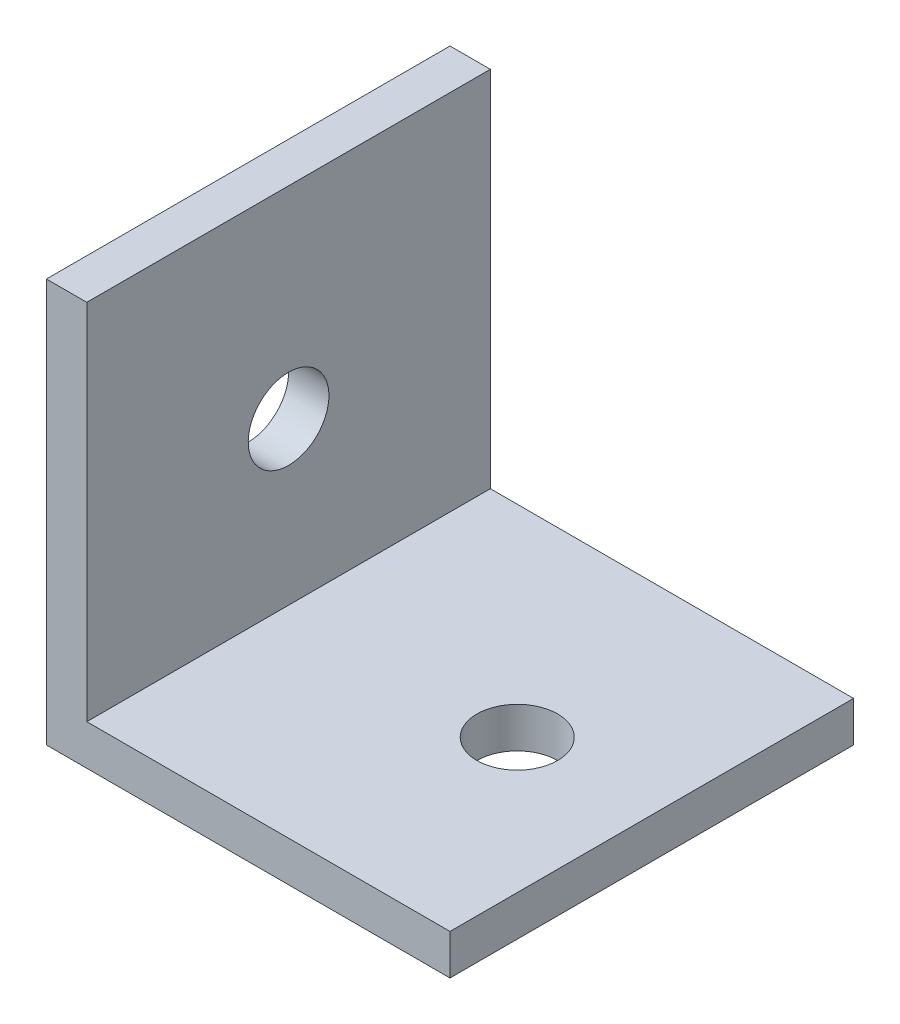
SolidWorks part; units mm, degrees
ref_plane "Plan de face" through (0, 0, 0) normal (0, 0, 1) x (1, 0, 0)
ref_plane "Plan de dessus" through (0, 0, 0) normal (0, 1, 0) x (1, 0, 0)
ref_plane "Plan de droite" through (0, 0, 0) normal (1, 0, 0) x (0, 0, -1)
sketch "Esquisse1" plane through (0, 0, 0) normal (0, 0, 1) x (1, 0, 0)
  line L0 (-11.9957, -0.6316) -> (-11.9957, -15.6316)
  line L1 (-11.9957, -15.6316) -> (3.0043, -15.6316)
  line L2 (3.0043, -15.6316) -> (3.0043, -14.1316)
  line L3 (3.0043, -14.1316) -> (-10.4957, -14.1316)
  line L4 (-10.4957, -14.1316) -> (-10.4957, -0.6316)
  line L5 (-10.4957, -0.6316) -> (-11.9957, -0.6316)
  dimension "D1" = 1.5
  dimension "D2" = 1.5
  dimension "D3" = 15
  dimension "D4" = 15
extrude "Extrusion1" add sketch "Esquisse1" along normal blind 15
sketch "Esquisse2" plane through (-11.9957, 0, 0) normal (-1, 0, 0) x (0, 0, 1)
  line L0 (15, -0.6316) -> (0, -0.6316) construction
  line L1 (0, -0.6316) -> (0, -15.6316) construction
  circle A0 centre (7.5, -8.1316) radius 1.5
  dimension "D1" = 7.5
  dimension "D2" = 7.5
extrude "Extrusion2" cut sketch "Esquisse2" against normal blind 15
sketch "Esquisse3" plane through (0, -15.6316, 0) normal (0, -1, 0) x (1, 0, 0)
  line L0 (-11.9957, 15) -> (-11.9957, 0) construction
  line L1 (-11.9957, 0) -> (3.0043, 0) construction
  circle A0 centre (-1.9957, 7.5) radius 1.5
  dimension "D1" = 10
  dimension "D2" = 7.5
extrude "Extrusion3" cut sketch "Esquisse3" against normal blind 15
